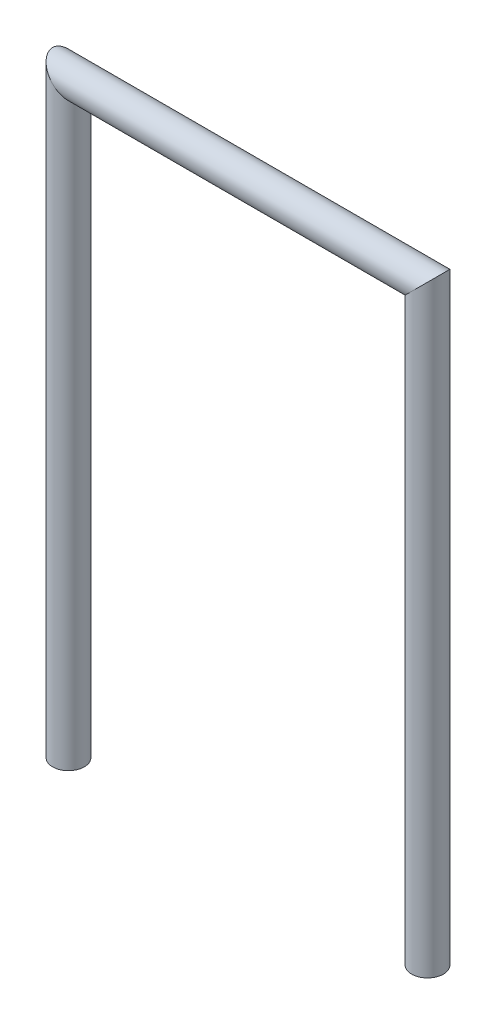
SolidWorks part; units mm, degrees
ref_plane "Front Plane" through (0, 0, 0) normal (0, 0, 1) x (1, 0, 0)
ref_plane "Top Plane" through (0, 0, 0) normal (0, 1, 0) x (1, 0, 0)
ref_plane "Right Plane" through (0, 0, 0) normal (1, 0, 0) x (0, 0, -1)
sketch "Sketch1" plane through (0, 0, 0) normal (0, 0, 1) x (1, 0, 0)
  line L0 (0, 0) -> (0, 560)
  line L1 (0, 560) -> (340, 560)
  line L2 (340, 560) -> (340, 0)
  dimension "D1" = 560
  dimension "D2" = 340
sketch "Sketch2" plane through (0, 0, 0) normal (0, 1, 0) x (1, 0, 0)
  circle A0 centre (0, 0) radius 15
  dimension "D1" = 30
sweep "Sweep1" add profiles "Sketch2" path "Sketch1"
sketch "Sketch3" plane through (0, 0, 0) normal (0, -1, 0) x (-1, 0, 0)
  line L0 (0, 0) -> (30, 0) construction
  line L1 (0, 0) -> (-340, 0) construction
  line L2 (-340, 0) -> (-370, 0) construction
  line L3 (-161.1587, 11.2708) -> (-161.1587, 70.6108) construction
  circle A0 centre (30, 0) radius 14
  circle A2 centre (-370, 0) radius 14
  dimension "D3" = 28
  dimension "D4" = 28
  dimension "D1" = 30
  dimension "D2" = 30
